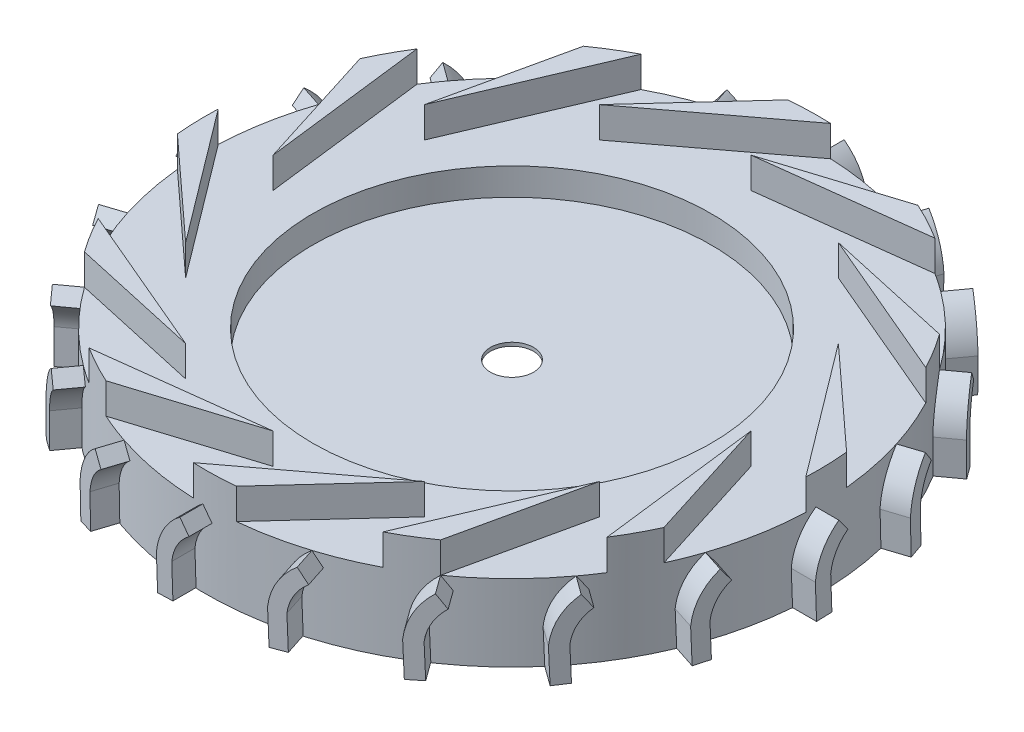
SolidWorks part; units mm, degrees
ref_plane "Front Plane" through (0, 0, 0) normal (0, 0, 1) x (1, 0, 0)
ref_plane "Top Plane" through (0, 0, 0) normal (0, 1, 0) x (1, 0, 0)
ref_plane "Right Plane" through (0, 0, 0) normal (1, 0, 0) x (0, 0, -1)
sketch "Sketch1" plane through (0, 0, 0) normal (1, 0, 0) x (0, 0, -1)
  line L0 (0, 26.2631) -> (0, -1.0485) construction
  line L1 (0, -1.0485) -> (-50.8, -1.0485)
  line L2 (-50.8, -1.0485) -> (-50.8, 11.6515)
  line L3 (-33.0001, 11.6515) -> (-50.8, 11.6515)
  line L4 (-33.0001, 11.6515) -> (-33.0001, 7.1515)
  line L5 (-33.0001, 7.1515) -> (0, 7.1515)
  line L6 (0, 7.1515) -> (0, -1.0485)
  dimension "D1" = 33.0001
  dimension "D2" = 50.8
  dimension "D3" = 4.5
  dimension "D4" = 12.7
revolve "Revolve1" add sketch "Sketch1" angle 360 about L0
sketch "Sketch2" plane through (0, 11.6515, 0) normal (0, 1, 0) x (1, 0, 0)
  line L8 (0, 39.6001) -> (19.9397, 39.6001) construction
  line L9 (0, 39.6001) -> (21.0453, 46.2356)
  line L10 (0, 39.6001) -> (27.1669, 42.9255)
  circle A0 centre (0, 0) radius 50.8 construction
  arc A1 (21.0453, 46.2356) -> (27.1669, 42.9255) centre (0, 0) cw
  circle A5 centre (0, 0) radius 33.0001 construction
  circle A7 centre (0, 0) radius 39.6001 construction
  point P9 (-2.4416, -40.4611)
  point P12 (0, 0)
  point P13 (0, 0)
  dimension "D1" = 66.0001
  dimension "D2" = 79.2001
  dimension "D3" = 17.5
extrude "Boss-Extrude1" add sketch "Sketch2" along normal blind 5.08
pattern_circular "CirPattern1" count 12 over 360 about axis through (0, 0, 0) along (0, 1, 0) of "Boss-Extrude1"
ref_plane "Plane1" through (0, 0, 49.53) normal (0, 0, 1) x (1, 0, 0)
sketch "Sketch3" plane through (0, 0, 49.53) normal (0, 0, 1) x (1, 0, 0)
  line L0 (0, 0) -> (0, 9.7621) construction
  line L1 (0, -55) -> (0, 55) construction
  line L5 (-21.0453, 11.6515) -> (0, 11.6515) construction
  line L6 (-50.8, -1.0485) -> (50.8, -1.0485) construction
  line L7 (-4.3287, 4.6923) -> (-4.1287, -1.0485)
  line L10 (-1.7845, 4.6163) -> (-1.5903, -0.9601)
  line L11 (1.0729, 9.6084) -> (-0.4363, 11.6515)
  line L12 (-4.1287, -1.0485) -> (-1.5903, -0.9601)
  arc A4 (-0.4363, 11.6515) -> (-4.3287, 4.6923) centre (5.3144, 3.8668) ccw
  arc A5 (1.0729, 9.6084) -> (-1.7845, 4.6163) centre (5.3144, 3.8668) ccw
  dimension "D1" = 2.54
extrude "Boss-Extrude2" add sketch "Sketch3" along normal blind 5.08 and the other way blind 0.254
pattern_circular "CirPattern16" count 20 over 360 about axis through (0, 0, 0) along (0, 1, 0) of "Boss-Extrude2"
sketch "Sketch4" plane through (0, 7.1515, 0) normal (0, 1, 0) x (1, 0, 0)
  circle A0 centre (0, 0) radius 3.5687
  dimension "D1" = 7.1374
extrude "Cut-Extrude1" cut sketch "Sketch4" against normal up to next
sketch "Sketch5" plane through (0, -1.0485, 0) normal (0, -1, 0) x (-1, 0, 0)
  circle A0 centre (0, 0) radius 38.1
  dimension "D1" = 76.2
extrude "Cut-Extrude2" cut sketch "Sketch5" against normal blind 7.62
